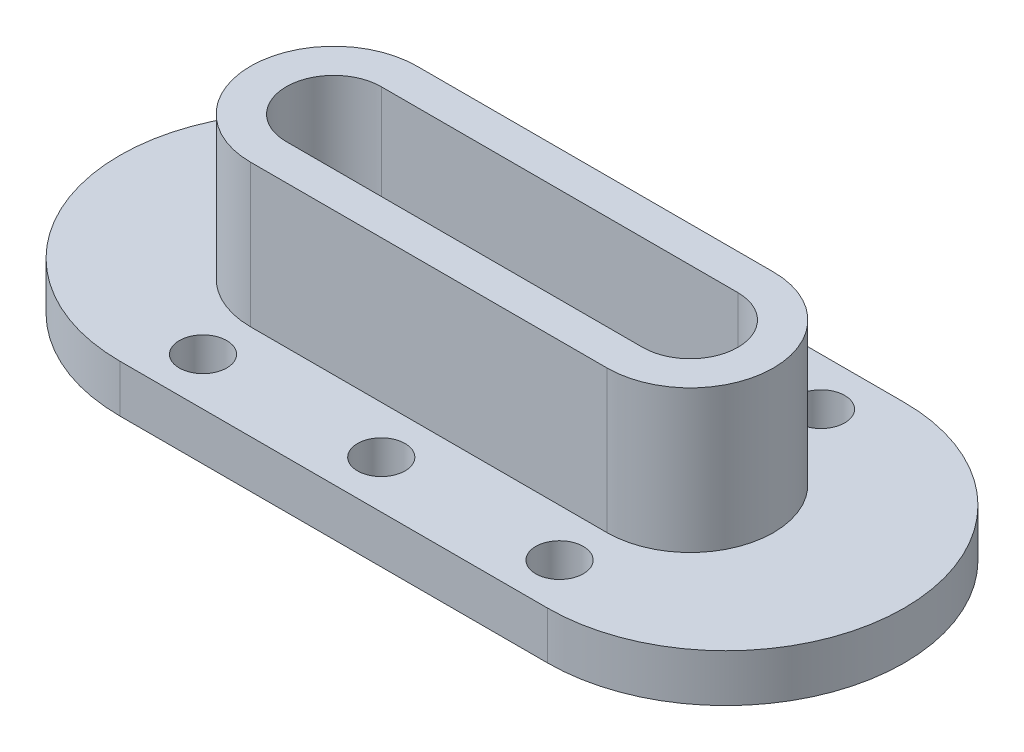
SolidWorks part; units mm, degrees
ref_plane "Front Plane" through (0, 0, 0) normal (0, 0, 1) x (1, 0, 0)
ref_plane "Top Plane" through (0, 0, 0) normal (0, 1, 0) x (1, 0, 0)
ref_plane "Right Plane" through (0, 0, 0) normal (1, 0, 0) x (0, 0, -1)
sketch "Sketch1" plane through (0, 0, 0) normal (0, 1, 0) x (1, 0, 0)
  line L0 (-90, 0) -> (90, 0) construction
  line L1 (-90, 75) -> (90, 75)
  line L2 (-90, -75) -> (90, -75)
  arc A0 (-90, 75) -> (-90, -75) centre (-90, 0) ccw
  arc A1 (90, -75) -> (90, 75) centre (90, 0) ccw
  point P3 (0, 0)
  point P8 (0, 0)
  dimension "D1" = 75
  dimension "D2" = 180
extrude "Boss-Extrude1" add sketch "Sketch1" along normal mid plane 20
sketch "Sketch2" plane through (0, 10, 0) normal (0, 1, 0) x (1, 0, 0)
  line L0 (-75, 0) -> (75, 0) construction
  line L1 (-75, 35) -> (75, 35)
  line L2 (-75, -35) -> (75, -35)
  line L3 (-75, 0) -> (75, 0) construction
  line L4 (-75, 20) -> (75, 20)
  line L5 (-75, -20) -> (75, -20)
  arc A0 (-75, 35) -> (-75, -35) centre (-75, 0) ccw
  arc A1 (75, -35) -> (75, 35) centre (75, 0) ccw
  arc A2 (-75, 20) -> (-75, -20) centre (-75, 0) ccw
  arc A3 (75, -20) -> (75, 20) centre (75, 0) ccw
  point P2 (0, 0)
  point P10 (0, 0)
  dimension "D2" = 35
  dimension "D3" = 20
  dimension "D1" = 150
extrude "Boss-Extrude2" add sketch "Sketch2" along normal blind 60
hole_wizard "Hole1" positions "Sketch3" profile "Sketch4" legacy end condition up to next
sketch "Sketch3" plane through (0, 10, 0) normal (0, 1, 0) x (1, 0, 0)
  point P0 (75, -55)
  point P2 (0, -55)
  point P4 (-75, -55)
  point P7 (0, 0)
  point P8 (0, 0)
  point P10 (74.9192, -54.2992)
  point P11 (0, -55)
  point P12 (-58.5205, -55)
  point P13 (74.6309, -55)
  dimension "D1" = 150
  dimension "D2" = 55
  dimension "D3" = 75
sketch "Sketch4" plane through (75, 10, 55) normal (1, 0, 0) x (0, 0, 1)
  line L0 (0, 0) -> (0, 20)
  line L1 (0, 20) -> (10, 20)
  line L2 (10, 20) -> (10, 0)
  line L3 (10, 0) -> (0, 0)
  line L4 (0, 110) -> (0, -10) construction
  dimension "Diameter" = 20
  dimension "Depth" = 20
mirror "Mirror1" about plane through (0, 0, 0) normal (0, 0, 1) of "Hole1"
hole_wizard "Hole2" positions "Sketch5" profile "Sketch6" legacy end condition up to next
sketch "Sketch5" plane through (0, 10, 0) normal (0, 1, 0) x (1, 0, 0)
  point P0 (0, 0)
  point P3 (75, 0)
  point P6 (-75, 0)
sketch "Sketch6" plane through (0, 10, 0) normal (1, 0, 0) x (0, 0, 1)
  line L0 (0, 0) -> (0, 20)
  line L1 (0, 20) -> (7.5, 20)
  line L2 (7.5, 20) -> (7.5, 0)
  line L3 (7.5, 0) -> (0, 0)
  line L4 (0, 110) -> (0, -10) construction
  dimension "Diameter" = 15
  dimension "Depth" = 20
